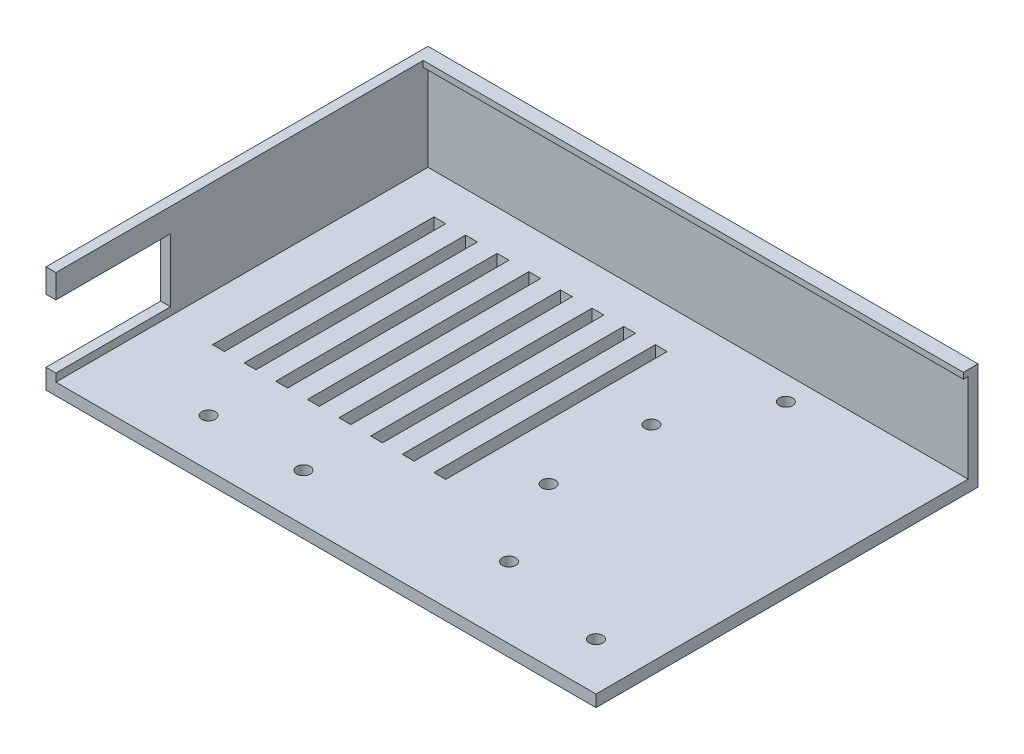
SolidWorks part; units mm, degrees
ref_plane "Front Plane" through (0, 0, 0) normal (0, 0, 1) x (1, 0, 0)
ref_plane "Top Plane" through (0, 0, 0) normal (0, 1, 0) x (1, 0, 0)
ref_plane "Right Plane" through (0, 0, 0) normal (1, 0, 0) x (0, 0, -1)
sketch "Sketch1" plane through (0, 0, 0) normal (0, 1, 0) x (1, 0, 0)
  line L1 (-139.1, -96.6) -> (139.1, -96.6)
  line L2 (-139.1, -96.6) -> (-139.1, 96.6)
  line L3 (-139.1, 96.6) -> (139.1, 96.6)
  line L4 (139.1, -96.6) -> (139.1, 96.6)
  line L5 (-139.1, -96.6) -> (139.1, 96.6) construction
  line L6 (-139.1, 96.6) -> (139.1, -96.6) construction
  point P0 (0, 0)
  dimension "D1" = 278.2
  dimension "D2" = 193.2
extrude "Shell Block" add sketch "Sketch1" along normal blind 27
ref_plane "Shell Front" through (0, 27, 0) normal (0, 1, 0) x (1, 0, 0)
sketch "Sketch2" plane through (0, 27, 0) normal (0, 1, 0) x (1, 0, 0)
  line L1 (-136.6, -92.9) -> (136.6, -92.9)
  line L2 (-136.6, -92.9) -> (-136.6, 92.9)
  line L3 (-136.6, 92.9) -> (136.6, 92.9)
  line L4 (136.6, -92.9) -> (136.6, 92.9)
  line L5 (-136.6, -92.9) -> (136.6, 92.9) construction
  line L6 (-136.6, 92.9) -> (136.6, -92.9) construction
  point P0 (0, 0)
  dimension "D1" = 273.2
  dimension "D2" = 185.8
extrude "Front Opening" cut sketch "Sketch2" against normal blind 1.5
ref_plane "Under Lip" through (0, 25.5, 0) normal (0, 1, 0) x (1, 0, 0)
sketch "Sketch3" plane through (0, 25.5, 0) normal (0, 1, 0) x (1, 0, 0)
  line L1 (-136.6, -94.1) -> (136.6, -94.1)
  line L2 (-136.6, -94.1) -> (-136.6, 94.1)
  line L3 (-136.6, 94.1) -> (136.6, 94.1)
  line L4 (136.6, -94.1) -> (136.6, 94.1)
  line L5 (-136.6, -94.1) -> (136.6, 94.1) construction
  line L6 (-136.6, 94.1) -> (136.6, -94.1) construction
  point P0 (0, 0)
  dimension "D1" = 273.2
  dimension "D2" = 188.2
extrude "Display Pocket" cut sketch "Sketch3" against normal blind 22.5
ref_plane "Back Inner" through (0, 3, 0) normal (0, 1, 0) x (1, 0, 0)
sketch "Sketch4" plane through (0, 3, 0) normal (0, 1, 0) x (1, 0, 0)
  line L1 (-69, 28) -> (-66, 28)
  line L2 (-69, 28) -> (-69, 84)
  line L3 (-69, 84) -> (-66, 84)
  line L4 (-66, 28) -> (-66, 84)
  line L6 (-69, -84) -> (-66, -84)
  line L7 (-69, -84) -> (-69, -28)
  line L8 (-69, -28) -> (-66, -28)
  line L9 (-66, -84) -> (-66, -28)
  line L11 (-77, 28) -> (-74, 28)
  line L12 (-77, 28) -> (-77, 84)
  line L13 (-77, 84) -> (-74, 84)
  line L14 (-74, 28) -> (-74, 84)
  line L16 (-77, -84) -> (-74, -84)
  line L17 (-77, -84) -> (-77, -28)
  line L18 (-77, -28) -> (-74, -28)
  line L19 (-74, -84) -> (-74, -28)
  line L21 (-85, 28) -> (-82, 28)
  line L22 (-85, 28) -> (-85, 84)
  line L23 (-85, 84) -> (-82, 84)
  line L24 (-82, 28) -> (-82, 84)
  line L26 (-85, -84) -> (-82, -84)
  line L27 (-85, -84) -> (-85, -28)
  line L28 (-85, -28) -> (-82, -28)
  line L29 (-82, -84) -> (-82, -28)
  line L31 (-93, 28) -> (-90, 28)
  line L32 (-93, 28) -> (-93, 84)
  line L33 (-93, 84) -> (-90, 84)
  line L34 (-90, 28) -> (-90, 84)
  line L36 (-93, -84) -> (-90, -84)
  line L37 (-93, -84) -> (-93, -28)
  line L38 (-93, -28) -> (-90, -28)
  line L39 (-90, -84) -> (-90, -28)
  line L41 (-101, 28) -> (-98, 28)
  line L42 (-101, 28) -> (-101, 84)
  line L43 (-101, 84) -> (-98, 84)
  line L44 (-98, 28) -> (-98, 84)
  line L46 (-101, -84) -> (-98, -84)
  line L47 (-101, -84) -> (-101, -28)
  line L48 (-101, -28) -> (-98, -28)
  line L49 (-98, -84) -> (-98, -28)
  line L51 (-109, 28) -> (-106, 28)
  line L52 (-109, 28) -> (-109, 84)
  line L53 (-109, 84) -> (-106, 84)
  line L54 (-106, 28) -> (-106, 84)
  line L56 (-109, -84) -> (-106, -84)
  line L57 (-109, -84) -> (-109, -28)
  line L58 (-109, -28) -> (-106, -28)
  line L59 (-106, -84) -> (-106, -28)
  line L61 (-117, 28) -> (-114, 28)
  line L62 (-117, 28) -> (-117, 84)
  line L63 (-117, 84) -> (-114, 84)
  line L64 (-114, 28) -> (-114, 84)
  line L66 (-117, -84) -> (-114, -84)
  line L67 (-117, -84) -> (-117, -28)
  line L68 (-117, -28) -> (-114, -28)
  line L69 (-114, -84) -> (-114, -28)
  line L71 (-125, 28) -> (-122, 28)
  line L72 (-125, 28) -> (-125, 84)
  line L73 (-125, 84) -> (-122, 84)
  line L74 (-122, 28) -> (-122, 84)
  line L76 (-125, -84) -> (-122, -84)
  line L77 (-125, -84) -> (-125, -28)
  line L78 (-125, -28) -> (-122, -28)
  line L79 (-122, -84) -> (-122, -28)
extrude "Vent Slots" cut sketch "Sketch4" against normal blind 4
sketch "Sketch5" plane through (0, 0, 0) normal (1, 0, 0) x (0, 0, -1)
  line L1 (-29, 5) -> (29, 5)
  line L2 (-29, 5) -> (-29, 21)
  line L3 (-29, 21) -> (29, 21)
  line L4 (29, 5) -> (29, 21)
extrude "Cable Exit (-X short side)" cut sketch "Sketch5" against normal blind 140.1
sketch "Sketch6" plane through (0, 3, 0) normal (0, 1, 0) x (1, 0, 0)
  circle A0 centre (-40, 18) radius 1.7
  circle A1 centre (-40, 88) radius 1.7
  circle A2 centre (40, 18) radius 1.7
  circle A3 centre (40, 88) radius 1.7
  circle A4 centre (-52, 40) radius 1.7
  circle A5 centre (-52, 66) radius 1.7
  circle A6 centre (52, 40) radius 1.7
  circle A7 centre (52, 66) radius 1.7
  circle A8 centre (-12, -82) radius 1.7
  circle A9 centre (12, -82) radius 1.7
  circle A10 centre (124, -12) radius 1.7
  circle A11 centre (124, 12) radius 1.7
  circle A12 centre (-12, -12) radius 1.7
  circle A13 centre (-12, 12) radius 1.7
  circle A14 centre (12, -12) radius 1.7
  circle A15 centre (12, 12) radius 1.7
  circle A16 centre (-110, 12) radius 1.7
  circle A17 centre (-110, -12) radius 1.7
  circle A18 centre (-86, 12) radius 1.7
  circle A19 centre (-86, -12) radius 1.7
extrude "Bolt Holes" cut sketch "Sketch6" against normal blind 4
sketch "Sketch7" plane through (0, 0, 0) normal (0, 1, 0) x (1, 0, 0)
  line L1 (200, -200) -> (0, -200)
  line L2 (200, -200) -> (200, 200)
  line L3 (200, 200) -> (0, 200)
  line L4 (0, -200) -> (0, 200)
extrude "Keep one half (X)" cut sketch "Sketch7" against normal through all and the other way through all
sketch "Sketch8" plane through (0, 0, 0) normal (0, 1, 0) x (1, 0, 0)
  line L1 (-200, 0) -> (200, 0)
  line L2 (-200, 0) -> (-200, -200)
  line L3 (-200, -200) -> (200, -200)
  line L4 (200, 0) -> (200, -200)
extrude "Keep one quarter (Z)" cut sketch "Sketch8" against normal through all and the other way through all
equation "\"DispL\"= 272.0"
equation "\"DispW\"= 187.0"
equation "\"DispT\"= 20.0"
equation "\"Clr\"= 0.6"
equation "\"Wall\"= 2.5"
equation "\"BackT\"= 3.0"
equation "\"CableRoom\"= 4.0"
equation "\"LipW\"= 1.2"
equation "\"LipT\"= 1.5"
equation "\"CableW\"= 58.0"
equation "\"CableH\"= 16.0"
equation "\"BoltD\"= 3.4"
equation "\"ShellL\"= \"DispL\" + 2 * \"Clr\" + 2 * \"Wall\""
equation "\"ShellW\"= \"DispW\" + 2 * \"Clr\" + 2 * \"Wall\""
equation "\"ShellH\"= \"BackT\" + \"DispT\" + \"CableRoom\""
equation "\"D1@Sketch1\" = \"ShellL\""
equation "\"D2@Sketch1\" = \"ShellW\""
equation "\"D1@Shell Block\" = \"ShellH\""
equation "\"D1@Shell Front\" = \"ShellH\""
equation "\"D1@Sketch2\" = \"DispL\" + 2 * \"Clr\""
equation "\"D2@Sketch2\" = \"DispW\" + 2 * \"Clr\" - 2 * \"LipW\""
equation "\"D1@Front Opening\" = \"LipT\""
equation "\"D1@Under Lip\" = \"ShellH\" - \"LipT\""
equation "\"D1@Sketch3\" = \"DispL\" + 2 * \"Clr\""
equation "\"D2@Sketch3\" = \"DispW\" + 2 * \"Clr\""
equation "\"D1@Display Pocket\" = \"ShellH\" - \"LipT\" - \"BackT\""
equation "\"D1@Back Inner\" = \"BackT\""
